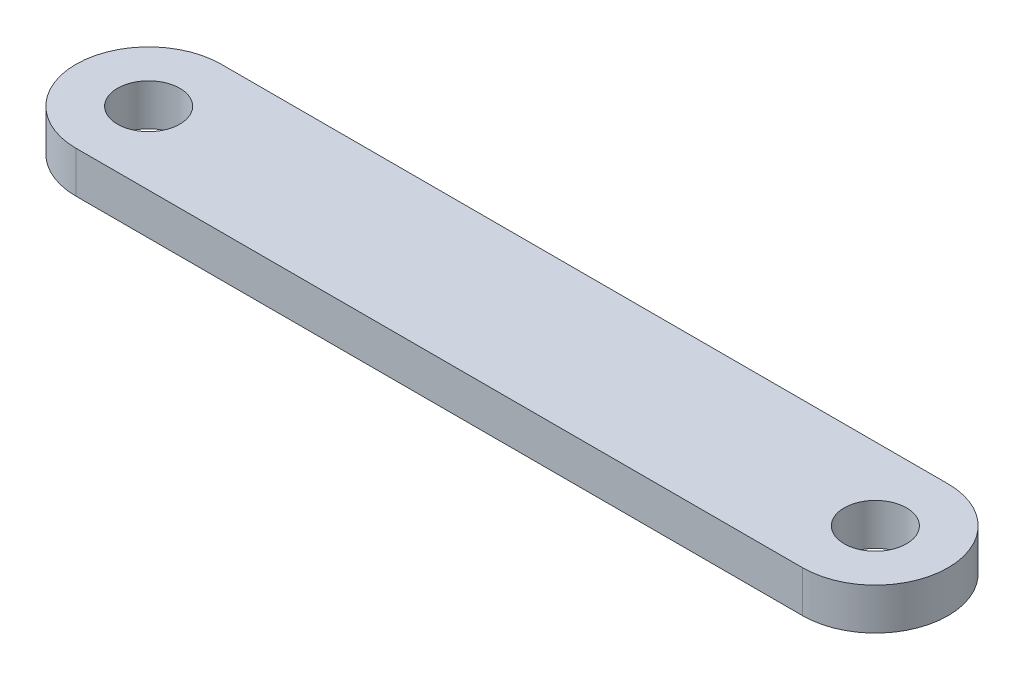
SolidWorks part; units mm, degrees
ref_plane "Front Plane" through (0, 0, 0) normal (0, 0, 1) x (1, 0, 0)
ref_plane "Top Plane" through (0, 0, 0) normal (0, 1, 0) x (1, 0, 0)
ref_plane "Right Plane" through (0, 0, 0) normal (1, 0, 0) x (0, 0, -1)
sketch "Sketch1" plane through (0, 0, 0) normal (0, 1, 0) x (1, 0, 0)
  line L0 (17.495, 0) -> (-17.495, 0) construction
  line L1 (17.495, -3.5) -> (-17.495, -3.5)
  line L2 (17.495, 3.5) -> (-17.495, 3.5)
  arc A0 (17.495, -3.5) -> (17.495, 3.5) centre (17.495, 0) ccw
  arc A1 (-17.495, 3.5) -> (-17.495, -3.5) centre (-17.495, 0) ccw
  circle A2 centre (-17.495, 0) radius 1.5
  circle A3 centre (17.495, 0) radius 1.5
  point P2 (0, 0)
  dimension "D2" = 3
  dimension "D3" = 3.5
  dimension "D1" = 34.99
extrude "Boss-Extrude1" add sketch "Sketch1" along normal blind 2
